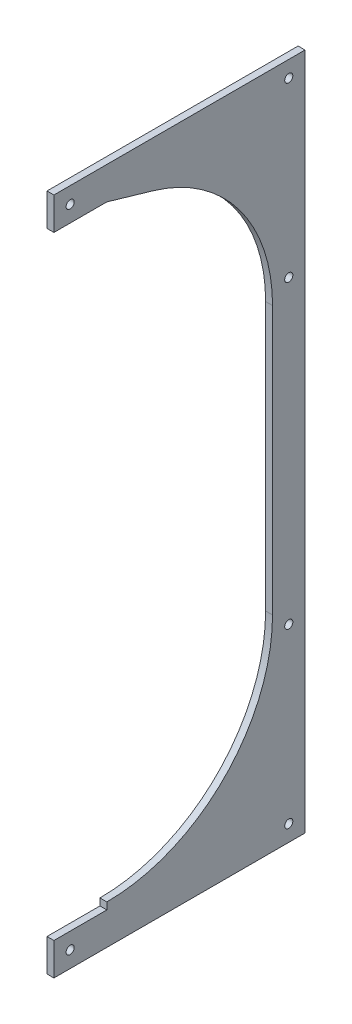
SolidWorks part; units mm, degrees
ref_plane "Front Plane" through (0, 0, 0) normal (0, 0, 1) x (1, 0, 0)
ref_plane "Top Plane" through (0, 0, 0) normal (0, 1, 0) x (1, 0, 0)
ref_plane "Right Plane" through (0, 0, 0) normal (1, 0, 0) x (0, 0, -1)
sketch "Sketch1" plane through (0, 0, 0) normal (1, 0, 0) x (0, 0, -1)
  line L0 (0, 0) -> (0, -139.192)
  line L1 (0, 0) -> (139.192, 0)
  line L2 (0, 0) -> (113.8047, -71.9099)
  line L3 (0, -129.54) -> (91.3565, -129.54)
  line L4 (-41.402, 369.885) -> (-41.402, 344.485)
  line L5 (129.54, 0) -> (139.192, 0)
  line L6 (0, 0) -> (154.94, 0)
  line L7 (0, 0) -> (0, -160.3502)
  line L8 (0, -160.3502) -> (154.94, -160.3502)
  line L9 (154.94, 0) -> (154.94, -160.3502)
  line L10 (154.94, 104.7674) -> (113.8047, 104.7674)
  line L11 (0, -129.54) -> (0, -160.3502)
  line L12 (0, -160.3502) -> (-8.3464, -160.3502)
  line L13 (0, 344.485) -> (-41.402, 344.485)
  line L14 (0, -160.3502) -> (-41.402, -160.3502)
  line L15 (0, -160.3502) -> (0, -134.9502)
  line L16 (0, -134.9502) -> (-41.402, -134.9502)
  line L17 (-41.402, -160.3502) -> (-41.402, -134.9502)
  line L18 (0, 369.885) -> (0, 344.485)
  line L19 (0, 369.885) -> (-41.402, 369.885)
  line L20 (0, 369.885) -> (-8.3464, 369.885)
  line L21 (0, 339.0748) -> (0, 369.885)
  line L22 (154.94, 209.5348) -> (154.94, 369.885)
  line L23 (0, 369.885) -> (154.94, 369.885)
  line L24 (0, 209.5348) -> (0, 369.885)
  line L25 (0, 209.5348) -> (154.94, 209.5348)
  line L26 (129.54, 209.5348) -> (139.192, 209.5348)
  line L27 (0, 339.0748) -> (91.3565, 339.0748)
  line L28 (0, 209.5348) -> (113.8047, 281.4447)
  line L29 (0, 209.5348) -> (139.192, 209.5348)
  line L30 (0, 209.5348) -> (0, 348.7268)
  line L31 (154.94, 0) -> (154.94, 209.5348)
  line L32 (129.54, 209.5348) -> (129.54, 0)
  line L33 (129.54, 0) -> (130.1531, 0.2952)
  circle A0 centre (0, 0) radius 129.54
  circle A1 centre (0, 0) radius 139.192
  circle A2 centre (-28.702, -147.6502) radius 3.175
  circle A3 centre (142.24, -12.7) radius 3.175
  circle A4 centre (142.24, -147.6502) radius 3.175
  circle A5 centre (142.24, 357.185) radius 3.175
  circle A6 centre (142.24, 222.2348) radius 3.175
  circle A7 centre (-28.702, 357.185) radius 3.175
  circle A8 centre (0, 209.5348) radius 139.192
  circle A9 centre (0, 209.5348) radius 129.54
  dimension "D1" = 9.652
  dimension "D4" = 134.62
  dimension "D5" = 30.8102
  dimension "D3" = 259.08
  dimension "D9" = 12.7
  dimension "D11" = 12.7
  dimension "D13" = 12.7
  dimension "D2" = 25.4
  dimension "D6" = 160.3502
  dimension "D7" = 41.402
  dimension "D8" = 25.4
  dimension "D10" = 12.7
  dimension "D12" = 12.7
  dimension "D14" = 12.7
  dimension "D15" = 104.7674
  dimension "D16" = 104.7674
extrude "Boss-Extrude3" add sketch "Sketch1" along normal blind 5.4102
sketch "Sketch2" plane through (5.4102, 0, 0) normal (1, 0, 0) x (0, 0, -1)
  line L0 (0, 344.485) -> (36.3113, 333.8815)
  line L1 (36.3113, 333.8815) -> (0, 339.0748)
  line L2 (0, 339.0748) -> (0, 344.485)
  arc A0 (129.54, 209.5348) -> (0, 339.0748) centre (0, 209.5348) ccw construction
extrude "Cut-Extrude1" cut sketch "Sketch2" against normal blind 5.4102
